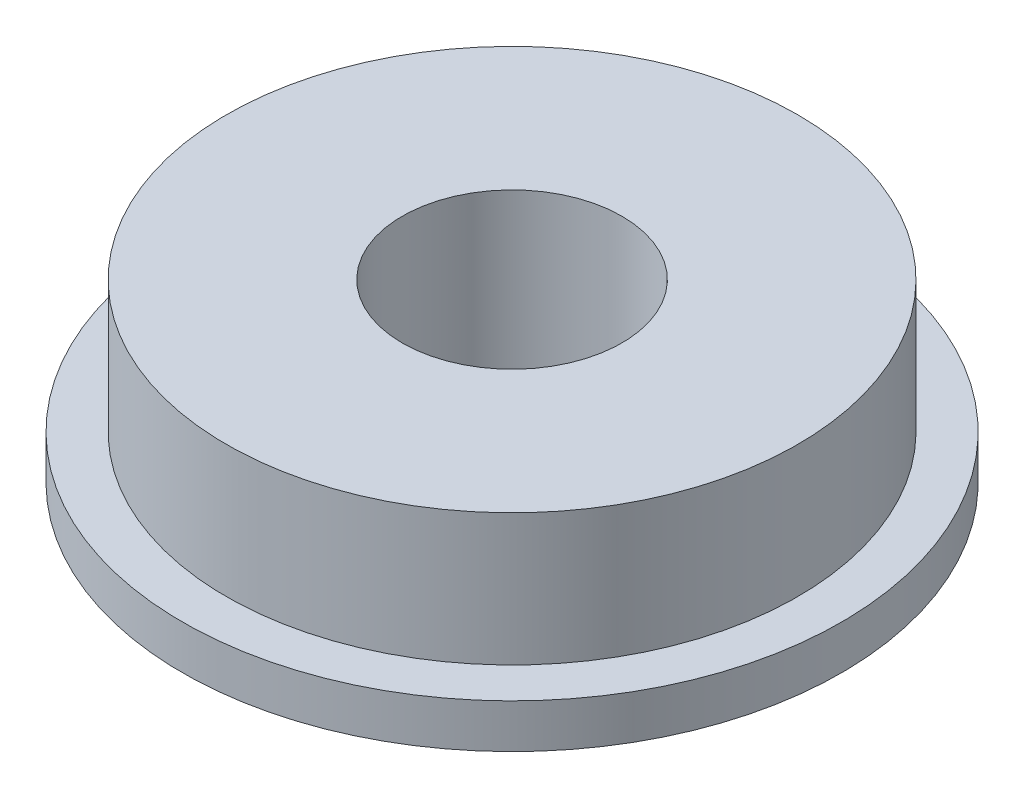
SolidWorks part; units mm, degrees
material "合金钢"
ref_plane "前视基准面" through (0, 0, 0) normal (0, 0, 1) x (1, 0, 0)
ref_plane "上视基准面" through (0, 0, 0) normal (0, 1, 0) x (1, 0, 0)
ref_plane "右视基准面" through (0, 0, 0) normal (1, 0, 0) x (0, 0, -1)
sketch "草图1" plane through (0, 0, 0) normal (0, 0, 1) x (1, 0, 0)
  line L0 (0, 0) -> (0, 4) construction
  line L1 (2.5, 0) -> (2.5, 4)
  line L2 (2.5, 4) -> (6.5, 4)
  line L3 (6.5, 4) -> (6.5, 1)
  line L4 (6.5, 1) -> (7.5, 1)
  line L5 (7.5, 1) -> (7.5, 0)
  line L6 (7.5, 0) -> (2.5, 0)
  dimension "D1" = 4
  dimension "D2" = 5
  dimension "D3" = 13
  dimension "D4" = 15
  dimension "D5" = 1
revolve "旋转1" add sketch "草图1" angle 360 about L0
